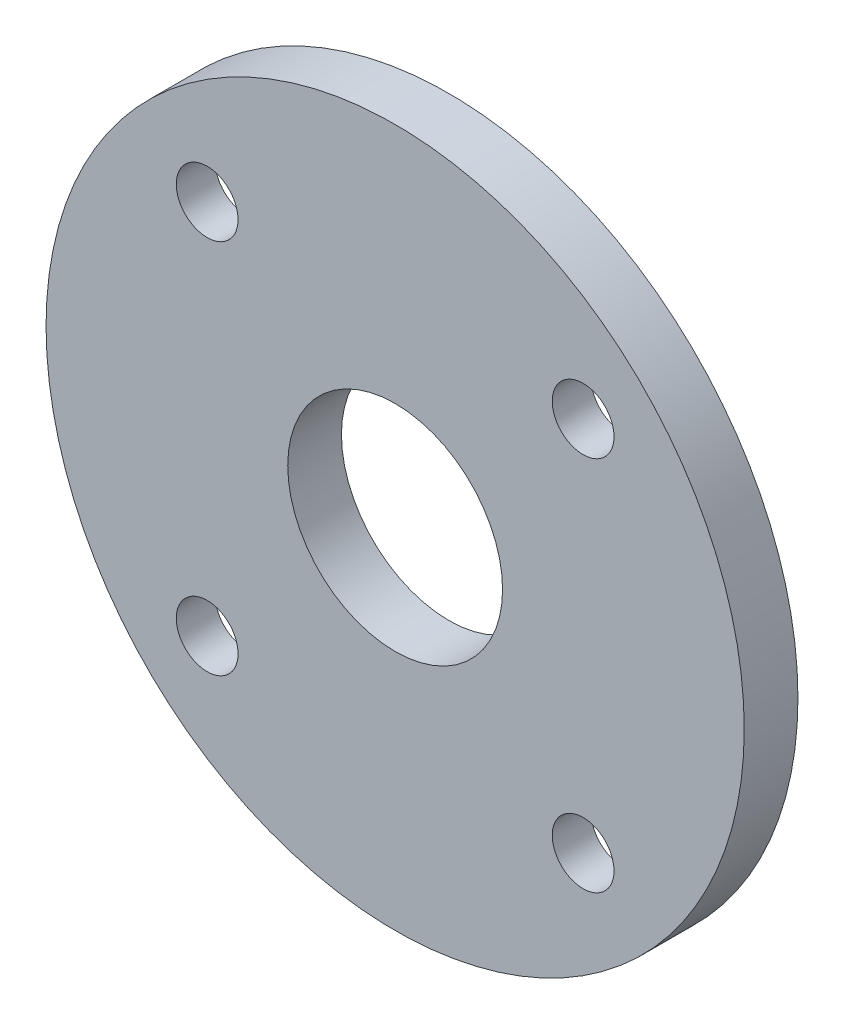
SolidWorks part; units mm, degrees
ref_plane "Front Plane" through (0, 0, 0) normal (0, 0, 1) x (1, 0, 0)
ref_plane "Top Plane" through (0, 0, 0) normal (0, 1, 0) x (1, 0, 0)
ref_plane "Right Plane" through (0, 0, 0) normal (1, 0, 0) x (0, 0, -1)
sketch "Cap_OD26_ID8_thickness2_profile" plane through (0, 0, 0) normal (0, 0, 1) x (1, 0, 0)
  circle A0 centre (0, 0) radius 13
  circle A1 centre (0, 0) radius 4
  dimension "D1" = 26
  dimension "D2" = 8
extrude "Cap_OD26_ID8_thickness2" add sketch "Cap_OD26_ID8_thickness2_profile" along normal blind 2
sketch "Four_M2_capture_holes_profile" plane through (0, 0, 0) normal (0, 0, 1) x (1, 0, 0)
  circle A0 centre (7, 7) radius 1.15
  circle A1 centre (-7, 7) radius 1.15
  circle A2 centre (-7, -7) radius 1.15
  circle A3 centre (7, -7) radius 1.15
  dimension "D1" = 2.3
  dimension "D2" = 2.3
  dimension "D3" = 2.3
  dimension "D4" = 2.3
  dimension "D5" = 7
  dimension "D6" = 7
  dimension "D7" = 7
  dimension "D8" = 7
extrude "Four_M2_capture_holes" cut sketch "Four_M2_capture_holes_profile" along normal through all from offset 50
sketch "Low_profile_head_seats" plane through (0, 0, 0) normal (0, 0, 1) x (1, 0, 0)
  circle A0 centre (7, 7) radius 2.1
  circle A1 centre (-7, 7) radius 2.1
  circle A2 centre (-7, -7) radius 2.1
  circle A3 centre (7, -7) radius 2.1
  dimension "D1" = 4.2
  dimension "D2" = 4.2
  dimension "D3" = 4.2
  dimension "D4" = 4.2
  dimension "D5" = 7
  dimension "D6" = 7
  dimension "D7" = 7
  dimension "D8" = 7
extrude "Head_recess_depth0p55" cut sketch "Low_profile_head_seats" along normal blind 0.55
